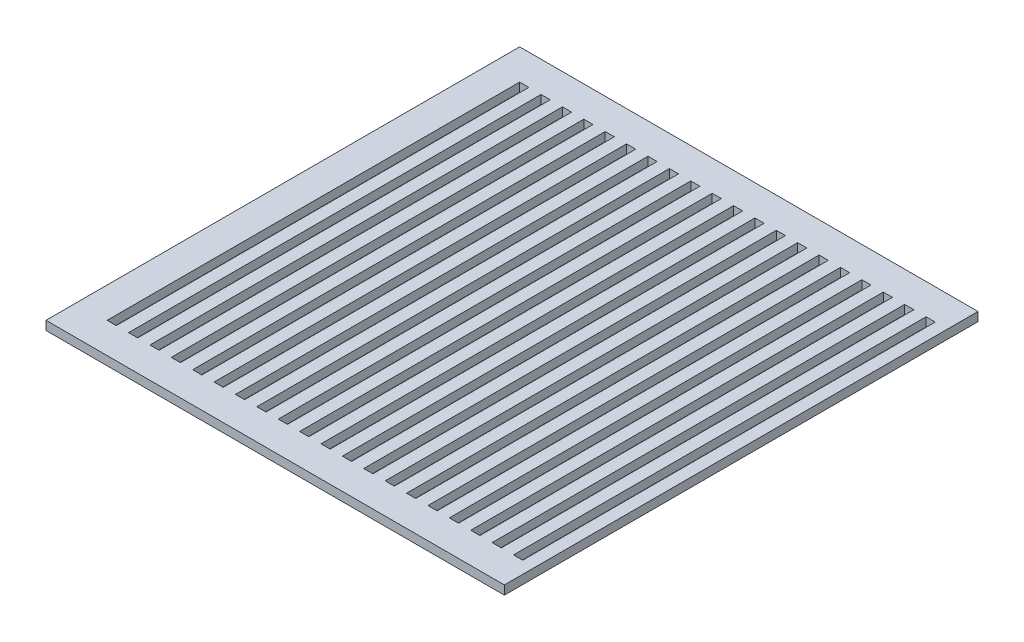
SolidWorks part; units mm, degrees
ref_plane "前视基准面" through (0, 0, 0) normal (0, 0, 1) x (1, 0, 0)
ref_plane "上视基准面" through (0, 0, 0) normal (0, 1, 0) x (1, 0, 0)
ref_plane "右视基准面" through (0, 0, 0) normal (1, 0, 0) x (0, 0, -1)
sketch "草图1" plane through (0, 0, 0) normal (0, 1, 0) x (1, 0, 0)
  line L1 (0, 0) -> (150, 0)
  line L2 (0, 0) -> (0, -155)
  line L3 (0, -155) -> (150, -155)
  line L4 (150, 0) -> (150, -155)
extrude "凸台-拉伸1" add sketch "草图1" along normal blind 2.9
sketch "草图2" plane through (0, 2.9, 0) normal (0, 1, 0) x (1, 0, 0)
  line L0 (0, 0) -> (0, -155) construction
  line L1 (150, 0) -> (0, 0) construction
  line L2 (0, -155) -> (150, -155) construction
  line L3 (17, -10) -> (17, -145)
  line L4 (10, -10) -> (13, -10)
  line L5 (10, -10) -> (10, -145)
  line L6 (10, -145) -> (13, -145)
  line L7 (13, -10) -> (13, -145)
  line L8 (17, -10) -> (20, -10)
  line L9 (20, -10) -> (20, -145)
  line L10 (17, -145) -> (20, -145)
  line L11 (24, -10) -> (24, -145)
  line L12 (24, -10) -> (27, -10)
  line L13 (27, -10) -> (27, -145)
  line L14 (24, -145) -> (27, -145)
  line L15 (31, -10) -> (31, -145)
  line L16 (31, -10) -> (34, -10)
  line L17 (34, -10) -> (34, -145)
  line L18 (31, -145) -> (34, -145)
  line L19 (38, -10) -> (38, -145)
  line L20 (38, -10) -> (41, -10)
  line L21 (41, -10) -> (41, -145)
  line L22 (38, -145) -> (41, -145)
  line L23 (45, -10) -> (45, -145)
  line L24 (45, -10) -> (48, -10)
  line L25 (48, -10) -> (48, -145)
  line L26 (45, -145) -> (48, -145)
  line L27 (52, -10) -> (52, -145)
  line L28 (52, -10) -> (55, -10)
  line L29 (55, -10) -> (55, -145)
  line L30 (52, -145) -> (55, -145)
  line L31 (59, -10) -> (59, -145)
  line L32 (59, -10) -> (62, -10)
  line L33 (62, -10) -> (62, -145)
  line L34 (59, -145) -> (62, -145)
  line L35 (66, -10) -> (66, -145)
  line L36 (66, -10) -> (69, -10)
  line L37 (69, -10) -> (69, -145)
  line L38 (66, -145) -> (69, -145)
  line L39 (73, -10) -> (73, -145)
  line L40 (73, -10) -> (76, -10)
  line L41 (76, -10) -> (76, -145)
  line L42 (73, -145) -> (76, -145)
  line L43 (80, -10) -> (80, -145)
  line L44 (80, -10) -> (83, -10)
  line L45 (83, -10) -> (83, -145)
  line L46 (80, -145) -> (83, -145)
  line L47 (87, -10) -> (87, -145)
  line L48 (87, -10) -> (90, -10)
  line L49 (90, -10) -> (90, -145)
  line L50 (87, -145) -> (90, -145)
  line L51 (94, -10) -> (94, -145)
  line L52 (94, -10) -> (97, -10)
  line L53 (97, -10) -> (97, -145)
  line L54 (94, -145) -> (97, -145)
  line L55 (101, -10) -> (101, -145)
  line L56 (101, -10) -> (104, -10)
  line L57 (104, -10) -> (104, -145)
  line L58 (101, -145) -> (104, -145)
  line L59 (108, -10) -> (108, -145)
  line L60 (108, -10) -> (111, -10)
  line L61 (111, -10) -> (111, -145)
  line L62 (108, -145) -> (111, -145)
  line L63 (115, -10) -> (115, -145)
  line L64 (115, -10) -> (118, -10)
  line L65 (118, -10) -> (118, -145)
  line L66 (115, -145) -> (118, -145)
  line L67 (122, -10) -> (122, -145)
  line L68 (122, -10) -> (125, -10)
  line L69 (125, -10) -> (125, -145)
  line L70 (122, -145) -> (125, -145)
  line L71 (129, -10) -> (129, -145)
  line L72 (129, -10) -> (132, -10)
  line L73 (132, -10) -> (132, -145)
  line L74 (129, -145) -> (132, -145)
  line L75 (136, -10) -> (136, -145)
  line L76 (136, -10) -> (139, -10)
  line L77 (139, -10) -> (139, -145)
  line L78 (136, -145) -> (139, -145)
  line L79 (143, -10) -> (143, -145)
  line L80 (143, -10) -> (146, -10)
  line L81 (146, -10) -> (146, -145)
  line L82 (143, -145) -> (146, -145)
  point P0 (0, -10)
  point P1 (10, 0)
  point P4 (0, -145)
  point P8 (10, -155)
  dimension "D1" = 10
  dimension "D2" = 10
  dimension "D3" = 10
  dimension "D4" = 10
  dimension "D5" = 20
extrude "切除-拉伸4" cut sketch "草图2" against normal blind 3
